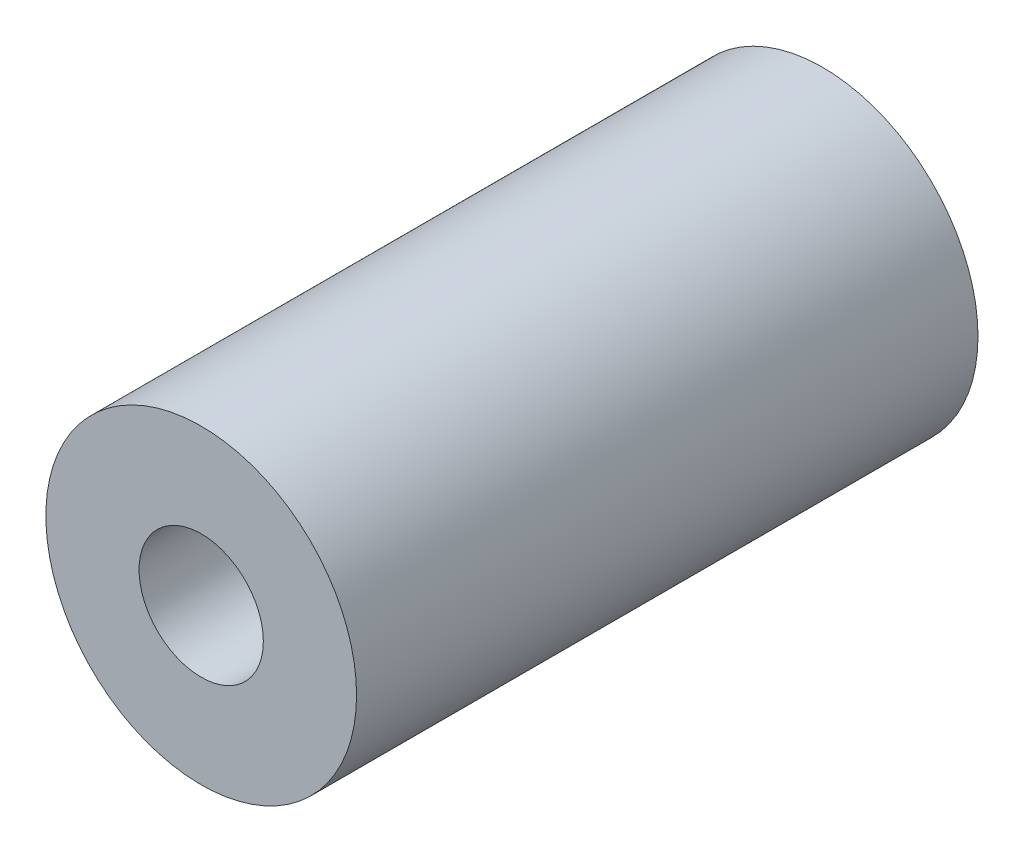
SolidWorks part; units mm, degrees
ref_plane "Front Plane" through (0, 0, 0) normal (0, 0, 1) x (1, 0, 0)
ref_plane "Top Plane" through (0, 0, 0) normal (0, 1, 0) x (1, 0, 0)
ref_plane "Right Plane" through (0, 0, 0) normal (1, 0, 0) x (0, 0, -1)
sketch "Sketch1" plane through (0, 0, 0) normal (0, 0, 1) x (1, 0, 0)
  circle A0 centre (0, 0) radius 7.9375
  circle A1 centre (0, 0) radius 3.175
  dimension "D1" = 15.875
  dimension "D2" = 6.35
extrude "Boss-Extrude1" add sketch "Sketch1" along normal blind 31.75
